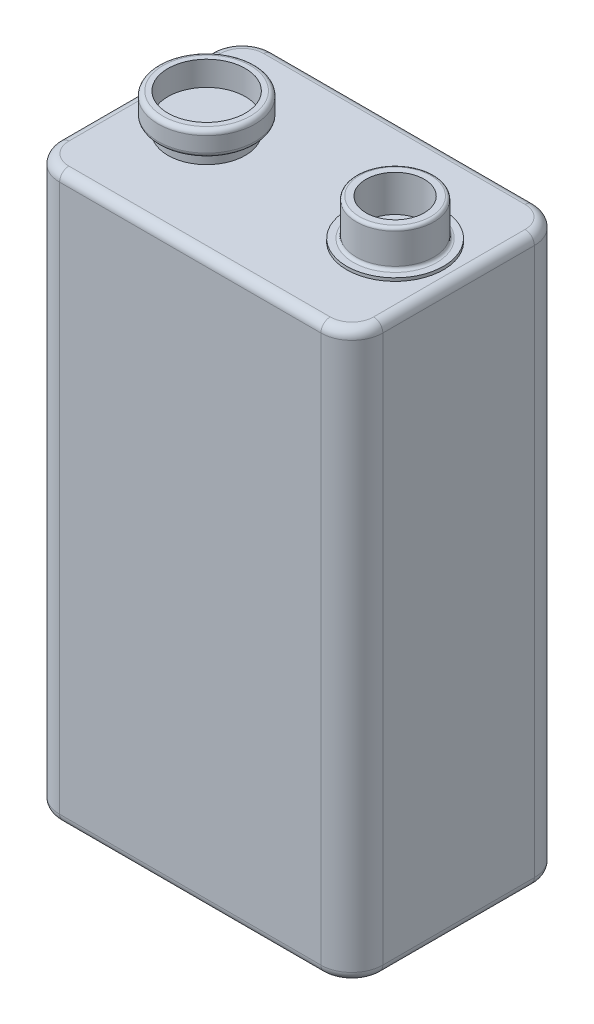
SolidWorks part; units mm, degrees
ref_plane "Front Plane" through (0, 0, 0) normal (0, 0, 1) x (1, 0, 0)
ref_plane "Top Plane" through (0, 0, 0) normal (0, 1, 0) x (1, 0, 0)
ref_plane "Right Plane" through (0, 0, 0) normal (1, 0, 0) x (0, 0, -1)
sketch "Sketch2" plane through (0, 0, 0) normal (0, 0, 1) x (1, 0, 0)
  line L1 (0, 0) -> (26.5, 0)
  line L2 (0, 0) -> (0, 46.4)
  line L3 (0, 46.4) -> (26.5, 46.4)
  line L4 (26.5, 0) -> (26.5, 46.4)
  dimension "D1" = 46.4
  dimension "D2" = 26.5
extrude "Boss-Extrude1" add sketch "Sketch2" against normal blind 17.5
fillet "Fillet1" radius 2.54 4 edges at (0, 23.2, -17.5) (0, 23.2, 0) (26.5, 23.2, -17.5) (26.5, 23.2, 0)
fillet "Fillet2" radius 0.762 16 edges at (25.7561, 46.4, -0.7439) (26.5, 46.4, -8.75) (25.7561, 46.4, -16.7561) (13.25, 46.4, -17.5) (0.7439, 46.4, -16.7561) (0, 46.4, -8.75) (0.7439, 46.4, -0.7439) (0.7439, 0, -0.7439) (13.25, 0, 0) (25.7561, 0, -0.7439) (26.5, 0, -8.75) (25.7561, 0, -16.7561) (13.25, 0, -17.5) (0.7439, 0, -16.7561) (0, 0, -8.75) (13.25, 46.4, 0)
sketch "Sketch3" plane through (0, 46.4, 0) normal (0, 1, 0) x (1, 0, 0)
  line L0 (25.738, 2.54) -> (25.738, 14.96) construction
  circle A0 centre (21.293, 8.75) radius 3.9688
  point P5 (25.738, 8.75)
  dimension "D1" = 7.9375
  dimension "D2" = 4.445
extrude "Boss-Extrude2" add sketch "Sketch3" along normal blind 0.254
sketch "Sketch4" plane through (0, 46.654, 0) normal (0, 1, 0) x (1, 0, 0)
  circle A0 centre (21.293, 8.75) radius 3.175
  circle A1 centre (21.293, 8.75) radius 2.3876
  dimension "D1" = 6.35
  dimension "D2" = 4.7752
extrude "Boss-Extrude3" add sketch "Sketch4" along normal blind 3
fillet "Fillet3" radius 0.254 2 edges at (21.293, 49.654, -5.575) (21.293, 46.654, -5.575)
sketch "Sketch5" plane through (0, 46.4, 0) normal (0, 1, 0) x (1, 0, 0)
  line L0 (0.762, 14.96) -> (0.762, 2.54) construction
  circle A0 centre (5.842, 8.75) radius 3.175
  point P5 (0.762, 8.75)
  dimension "D2" = 6.35
  dimension "D1" = 5.08
extrude "Boss-Extrude4" add sketch "Sketch5" along normal blind 1
sketch "Sketch6" plane through (0, 47.4, 0) normal (0, 1, 0) x (1, 0, 0)
  circle A0 centre (5.842, 8.75) radius 3.9688
  circle A1 centre (5.842, 8.75) radius 3.175
  dimension "D1" = 7.9375
  dimension "D2" = 6.35
extrude "Boss-Extrude5" add sketch "Sketch6" along normal blind 2 separate body
fillet "Fillet4" radius 0.381 2 edges at (5.842, 49.4, -4.7812) (5.842, 47.4, -4.7812)
